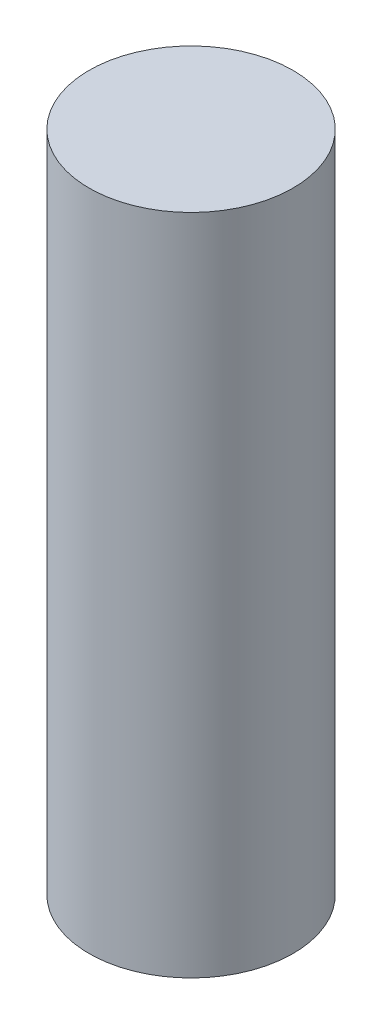
SolidWorks part; units mm, degrees
ref_plane "Front Plane" through (0, 0, 0) normal (0, 0, 1) x (1, 0, 0)
ref_plane "Top Plane" through (0, 0, 0) normal (0, 1, 0) x (1, 0, 0)
ref_plane "Right Plane" through (0, 0, 0) normal (1, 0, 0) x (0, 0, -1)
sketch "Sketch1" plane through (0, 0, 0) normal (0, 1, 0) x (1, 0, 0)
  circle A0 centre (0, 0) radius 1
  dimension "D1" = 2
extrude "Boss-Extrude1" add sketch "Sketch1" along normal blind 6.5
